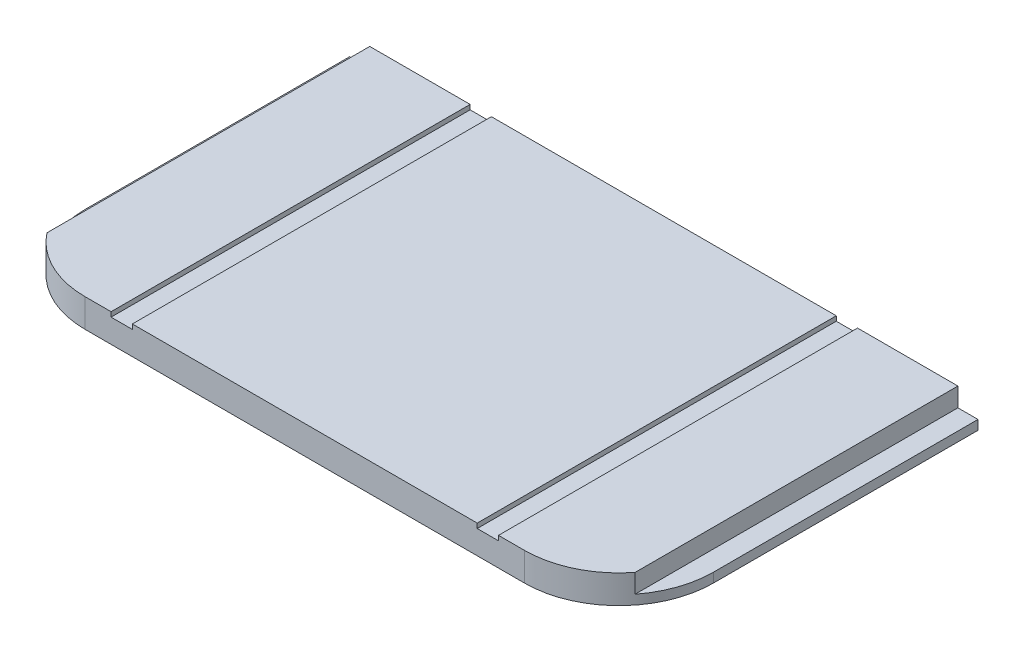
SolidWorks part; units mm, degrees
material "MDF"
ref_plane "Front Plane" through (0, 0, 0) normal (0, 0, 1) x (1, 0, 0)
ref_plane "Top Plane" through (0, 0, 0) normal (0, 1, 0) x (1, 0, 0)
ref_plane "Right Plane" through (0, 0, 0) normal (1, 0, 0) x (0, 0, -1)
sketch "Sketch1" plane through (0, 0, 0) normal (0, 1, 0) x (1, 0, 0)
  line L1 (-211.1375, -120.65) -> (211.1375, -120.65)
  line L2 (-211.1375, -120.65) -> (-211.1375, 120.65)
  line L3 (-211.1375, 120.65) -> (211.1375, 120.65)
  line L4 (211.1375, -120.65) -> (211.1375, 120.65)
  line L5 (-211.1375, -120.65) -> (211.1375, 120.65) construction
  line L6 (-211.1375, 120.65) -> (211.1375, -120.65) construction
  point P0 (0, 0)
  dimension "D1" = 422.275
  dimension "D2" = 241.3
extrude "Boss-Extrude1" add sketch "Sketch1" along normal blind 19.05
sketch "Sketch2" plane through (0, 0, 120.65) normal (0, 0, 1) x (1, 0, 0)
  line L0 (-211.1375, 19.05) -> (211.1375, 19.05) construction
  line L1 (-211.1375, 19.05) -> (-197.6438, 19.05)
  line L2 (-211.1375, 19.05) -> (-211.1375, 15.875)
  line L3 (-211.1375, 15.875) -> (-197.6438, 15.875)
  line L4 (-197.6438, 19.05) -> (-197.6438, 15.875)
  line L5 (-130.175, 19.05) -> (-115.8875, 19.05)
  line L6 (-130.175, 19.05) -> (-130.175, 15.875)
  line L7 (-130.175, 15.875) -> (-115.8875, 15.875)
  line L8 (-115.8875, 19.05) -> (-115.8875, 15.875)
  line L9 (-211.1375, 19.05) -> (-211.1375, 0) construction
  line L10 (115.8875, 19.05) -> (130.175, 19.05)
  line L11 (115.8875, 19.05) -> (115.8875, 15.875)
  line L12 (115.8875, 15.875) -> (130.175, 15.875)
  line L13 (130.175, 19.05) -> (130.175, 15.875)
  line L14 (211.1375, 19.05) -> (197.6437, 19.05)
  line L15 (211.1375, 19.05) -> (211.1375, 15.875)
  line L16 (211.1375, 15.875) -> (197.6437, 15.875)
  line L17 (197.6437, 19.05) -> (197.6437, 15.875)
  line L18 (211.1375, 19.05) -> (211.1375, 0) construction
  dimension "D1" = 13.4937
  dimension "D2" = 3.175
  dimension "D3" = 95.25
  dimension "D4" = 95.25
  dimension "D5" = 14.2875
  dimension "D6" = 13.4937
extrude "Cut-Extrude1" cut sketch "Sketch2" against normal up to next
fillet "Fillet1" radius 63.5 2 edges at (211.1375, 7.9375, 120.65) (-211.1375, 7.9375, 120.65)
sketch "Sketch3" plane through (0, 0, -120.65) normal (0, 0, -1) x (-1, 0, 0)
  line L1 (-197.6437, 15.875) -> (-211.1375, 15.875)
  line L2 (-197.6437, 15.875) -> (-197.6437, 6.35)
  line L3 (-197.6437, 6.35) -> (-211.1375, 6.35)
  line L4 (-211.1375, 15.875) -> (-211.1375, 6.35)
  line L5 (211.1375, 15.875) -> (211.1375, 0) construction
  line L6 (197.6438, 15.875) -> (211.1375, 15.875)
  line L7 (197.6438, 15.875) -> (197.6438, 6.35)
  line L8 (197.6438, 6.35) -> (211.1375, 6.35)
  line L9 (211.1375, 15.875) -> (211.1375, 6.35)
  line L10 (-211.1375, 15.875) -> (-211.1375, 0) construction
  line L11 (130.175, 19.05) -> (197.6438, 19.05) construction
  dimension "D1" = 12.7
extrude "Cut-Extrude2" cut sketch "Sketch3" against normal up to next
